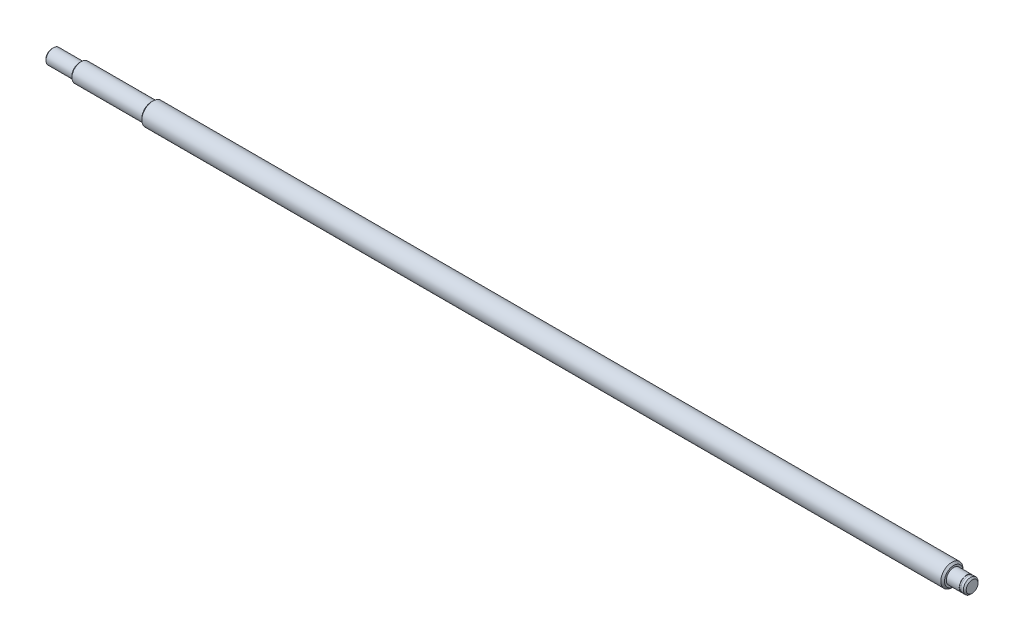
SolidWorks part; units mm, degrees
material "1.4057 (X17CrNi16-2)"
ref_plane "Plan de face" through (0, 0, 0) normal (0, 0, 1) x (1, 0, 0)
ref_plane "Plan de dessus" through (0, 0, 0) normal (0, 1, 0) x (1, 0, 0)
ref_plane "Plan de droite" through (0, 0, 0) normal (1, 0, 0) x (0, 0, -1)
sketch "Esquisse1" plane through (0, 0, 0) normal (0, 0, 1) x (1, 0, 0)
  line L0 (-511.9709, 0) -> (511.9709, 0) construction
  line L1 (-250, 0) -> (-250, 3.2)
  line L2 (-249.2, 4) -> (-235, 4)
  line L3 (-235, 4) -> (-235, 4.1)
  line L4 (-234.1, 5) -> (-196, 5)
  line L5 (-196, 5) -> (-196, 5.1)
  line L6 (-195.1, 6) -> (239, 6)
  line L7 (-250, 3.2) -> (-249.2, 4)
  line L8 (240, 5) -> (240, 4)
  line L9 (240, 4) -> (247, 4)
  line L10 (250, 3.2) -> (250, 0)
  line L11 (247, 4) -> (247, 3.8)
  line L12 (247, 3.8) -> (247.9, 3.8)
  line L13 (247.9, 3.8) -> (247.9, 4)
  line L14 (247.9, 4) -> (249.2, 4)
  line L15 (249.2, 4) -> (250, 3.2)
  line L16 (239, 6) -> (240, 5)
  line L17 (-196, 5.1) -> (-195.1, 6)
  line L18 (-235, 4.1) -> (-234.1, 5)
  line L19 (-250, 0) -> (250, 0)
  point P4 (0, 0)
  point P6 (-250, 4)
  point P7 (240, 6)
  point P9 (-235, 5)
  point P11 (-196, 6)
  point P14 (250, 4)
  point P28 (-250, 1.6)
  dimension "D1" = 4
  dimension "D2" = 5
  dimension "D3" = 6
  dimension "D4" = 0.8
  dimension "D5" = 45
  dimension "D6" = 15
  dimension "D7" = 39
  dimension "D8" = 4
  dimension "D9" = 10
  dimension "D10" = 7
  dimension "D11" = 0.9
  dimension "D12" = 0.2
  dimension "D13" = 0.8
  dimension "D14" = 45
  dimension "D15" = 1
  dimension "D16" = 45
  dimension "D17" = 0.9
  dimension "D18" = 45
  dimension "D19" = 0.9
  dimension "D20" = 45
  dimension "D21" = 500
  dimension "D22" = 250
revolve "Révolution1" add sketch "Esquisse1" angle 360 about L0
